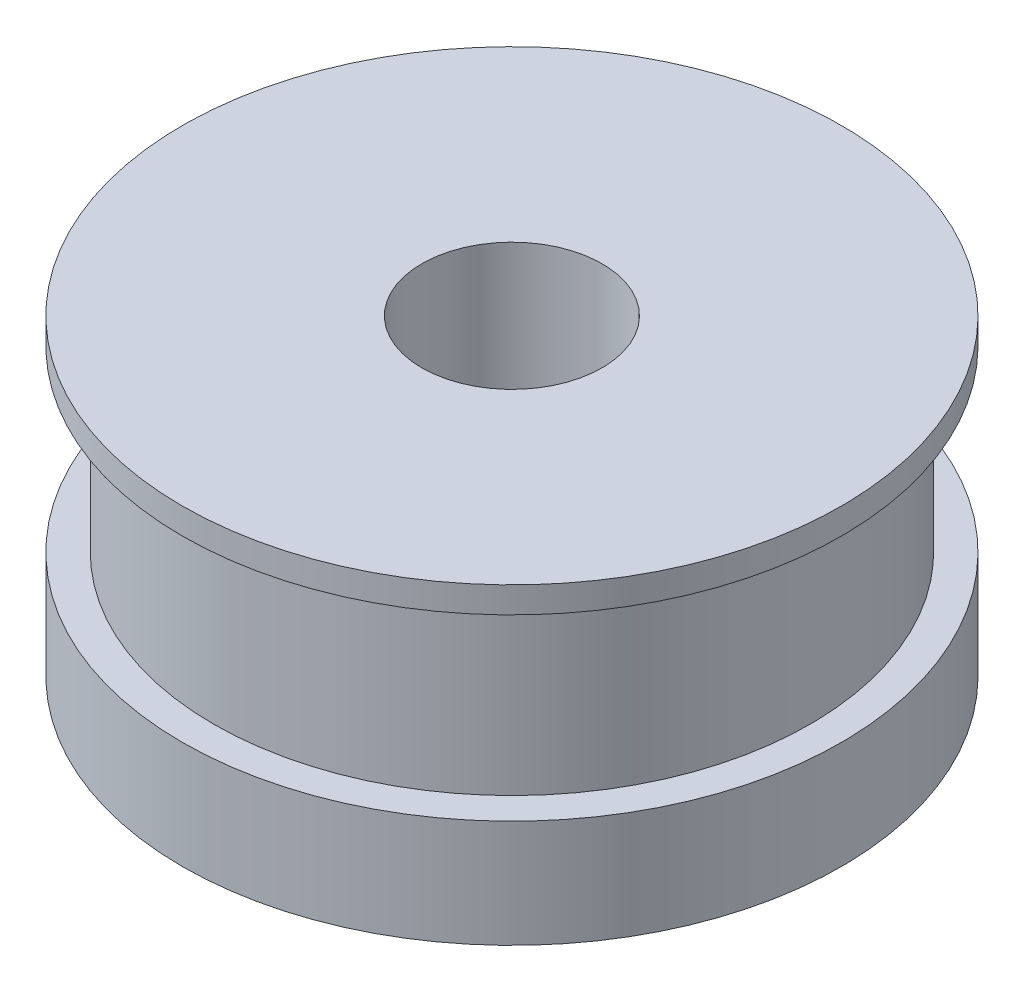
SolidWorks part; units mm, degrees
ref_plane "Front" through (0, 0, 0) normal (0, 0, 1) x (1, 0, 0)
ref_plane "Top" through (0, 0, 0) normal (0, 1, 0) x (1, 0, 0)
ref_plane "Right" through (0, 0, 0) normal (1, 0, 0) x (0, 0, -1)
sketch "Sketch1" plane through (0, 0, 0) normal (1, 0, 0) x (0, 0, -1)
  line L0 (0, 10.3155) -> (0, -11.35) construction
  line L1 (-13.3377, 0) -> (15.1571, 0) construction
  line L2 (17.19, -5.15) -> (17.19, 5.15)
  line L3 (19, 5.15) -> (19, 6.65)
  line L5 (17.19, 5.15) -> (19, 5.15)
  line L6 (5.2, 6.65) -> (5.2, -6.65)
  line L7 (17.19, -5.15) -> (19, -5.15)
  line L14 (19, 6.65) -> (10.28, 6.65)
  line L17 (10.28, 6.65) -> (5.2, 6.65)
  line L18 (19, -5.15) -> (19, -11.35)
  line L19 (19, -11.35) -> (5.2, -11.35)
  line L20 (5.2, -11.35) -> (5.2, -6.65)
  point P11 (17.19, 0)
  point P15 (5.2, 0)
  dimension "D1" = 1.5
  dimension "D2" = 6.2
  dimension "D3" = 19
  dimension "D5" = 5.2
  dimension "D6" = 10.3
revolve "Revolve1" add sketch "Sketch1" angle 360 about L0
sketch "Sketch2" plane through (0, -11.35, 0) normal (0, -1, 0) x (-1, 0, 0)
  line L0 (8, 0) -> (-8, 0) construction
  line L1 (0, -8) -> (0, 8) construction
  circle A0 centre (0, 0) radius 8
hole_wizard "M3 Tapped Hole1" positions "Sketch3" profile "Sketch4" tap size "M3" standard "ISO"
sketch "Sketch3" plane through (0, -11.35, 0) normal (0, -1, 0) x (-1, 0, 0)
  point P0 (0, -8)
  point P3 (-8, 0)
  point P6 (0, 8)
  point P9 (8, 0)
sketch "Sketch4" plane through (0, -11.35, 8) normal (1, 0, 0) x (0, 0, -1)
  line L0 (0, 0) -> (0, 4.7511)
  line L1 (0, 4.7511) -> (1.25, 4)
  line L2 (1.25, 4) -> (1.25, 0)
  line L5 (1.25, 0) -> (0, 0)
  line L10 (0, 4.7511) -> (-1.25, 4) construction
  line L11 (0, -6.35) -> (0, 107.95) construction
  dimension "Tap Drill Dia." = 2.5
  dimension "Tap Drill Depth" = 4
  dimension "Drill Angle" = 118
cosmetic thread "Hole Thread1" parameters "D1"=3.6, "D2"=3
cosmetic thread "Hole Thread2" parameters "D1"=3.6, "D2"=3
cosmetic thread "Hole Thread3" parameters "D1"=3.6, "D2"=3
cosmetic thread "Hole Thread4" parameters "D1"=3.6, "D2"=3
